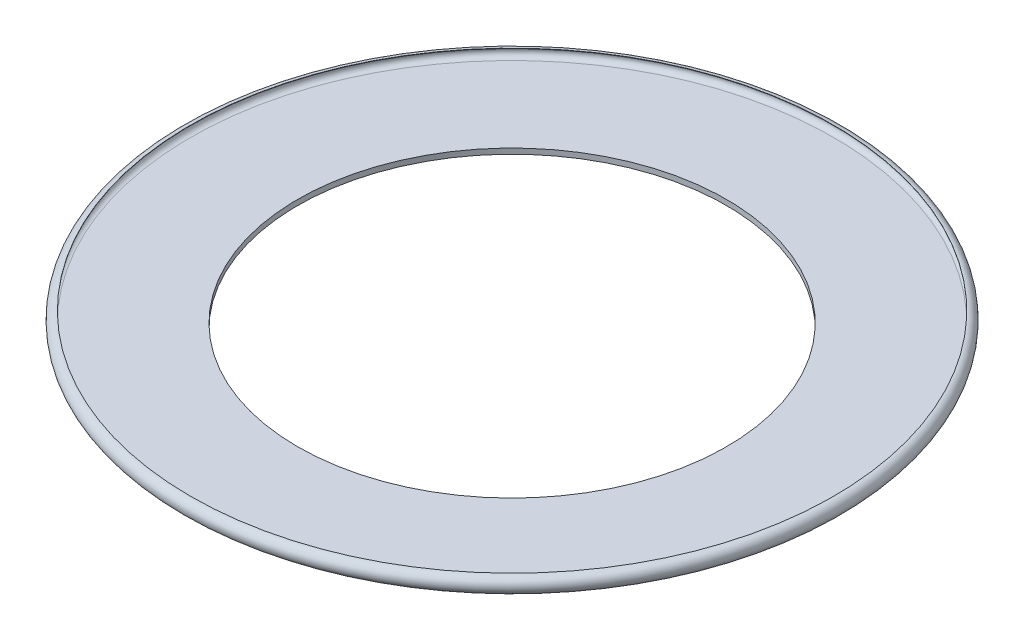
SolidWorks part; units mm, degrees
ref_plane "Front Plane" through (0, 0, 0) normal (0, 0, 1) x (1, 0, 0)
ref_plane "Top Plane" through (0, 0, 0) normal (0, 1, 0) x (1, 0, 0)
ref_plane "Right Plane" through (0, 0, 0) normal (1, 0, 0) x (0, 0, -1)
sketch "Sketch1" plane through (0, 0, 0) normal (0, 1, 0) x (1, 0, 0)
  circle A0 centre (0, 0) radius 101.6
  circle A1 centre (0, 0) radius 152.4
  dimension "D1" = 304.8
  dimension "D2" = 203.2
extrude "Boss-Extrude1" add sketch "Sketch1" along normal blind 2.54
sketch "Sketch3" plane through (0, 0, 0) normal (1, 0, 0) x (0, 0, -1)
  line L0 (-152.4, 7.62) -> (-152.4, 7.4676)
  line L1 (0, 70.5483) -> (0, -57.594) construction
  line L2 (-152.4, 2.54) -> (-152.4, 0)
  line L3 (-152.4, 11.4395) -> (-152.4, -1.4319) construction
  line L4 (-152.4, 2.54) -> (0, 2.54) construction
  arc A0 (-152.4, 0) -> (-152.4, 7.62) centre (-152.4, 3.81) cw
  arc A1 (-152.4, 7.4676) -> (-152.4, 2.54) centre (-152.4, 5.0038) ccw
  dimension "D1" = 3.81
  dimension "D2" = 2.4638
  dimension "D3" = 0.1524
revolve "Revolve1" add sketch "Sketch3" angle 360 about L1
